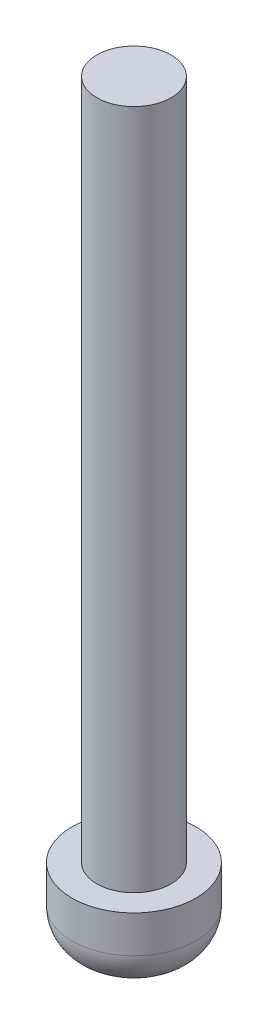
SolidWorks part; units mm, degrees
ref_plane "Front Plane" through (0, 0, 0) normal (0, 0, 1) x (1, 0, 0)
ref_plane "Top Plane" through (0, 0, 0) normal (0, 1, 0) x (1, 0, 0)
ref_plane "Right Plane" through (0, 0, 0) normal (1, 0, 0) x (0, 0, -1)
sketch "Sketch1" plane through (0, 0, 0) normal (0, 1, 0) x (1, 0, 0)
  circle A0 centre (0, 0) radius 5
  dimension "D1" = 10
extrude "Boss-Extrude1" add sketch "Sketch1" along normal blind 6
sketch "Sketch2" plane through (0, 6, 0) normal (0, 1, 0) x (1, 0, 0)
  circle A0 centre (0, 0) radius 3
  dimension "D1" = 6
extrude "Boss-Extrude2" add sketch "Sketch2" along normal blind 55
fillet "Fillet1" radius 3 1 edges at (0, 0, 5)
